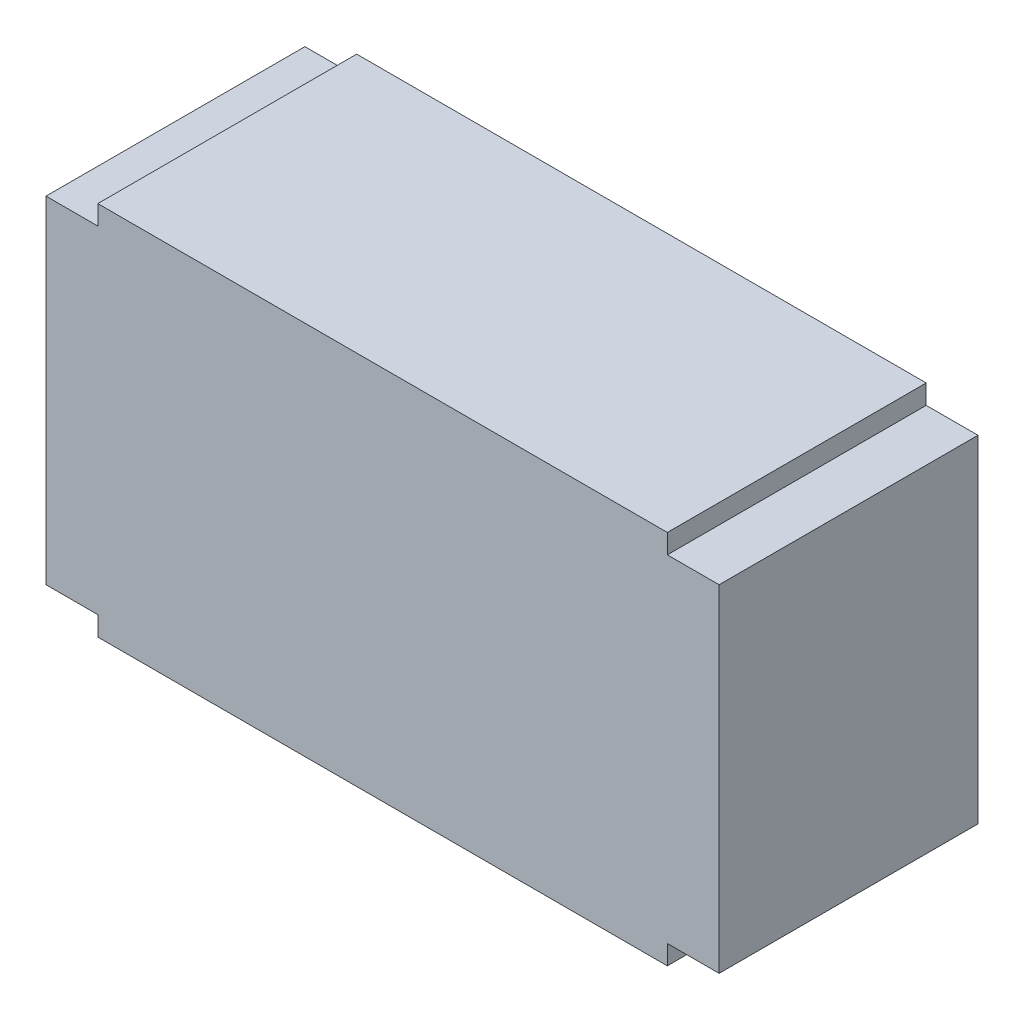
SolidWorks part; units mm, degrees
ref_plane "前视基准面" through (0, 0, 0) normal (0, 0, 1) x (1, 0, 0)
ref_plane "上视基准面" through (0, 0, 0) normal (0, 1, 0) x (1, 0, 0)
ref_plane "右视基准面" through (0, 0, 0) normal (1, 0, 0) x (0, 0, -1)
sketch "草图1" plane through (0, 0, 0) normal (0, 0, 1) x (1, 0, 0)
  line L0 (-1.3, 0.65) -> (-1.1, 0.65)
  line L1 (-1.1, 0.65) -> (-1.1, 0.725)
  line L2 (-1.1, 0.725) -> (1.1, 0.725)
  line L3 (1.1, 0.725) -> (1.1, 0.65)
  line L4 (1.1, 0.65) -> (1.3, 0.65)
  line L5 (1.3, 0.65) -> (1.3, -0.65)
  line L6 (1.3, -0.65) -> (1.1, -0.65)
  line L7 (1.1, -0.65) -> (1.1, -0.725)
  line L8 (1.1, -0.725) -> (-1.1, -0.725)
  line L9 (-1.1, -0.725) -> (-1.1, -0.65)
  line L10 (-1.1, -0.65) -> (-1.3, -0.65)
  line L11 (-1.3, -0.65) -> (-1.3, 0.65)
extrude "Component_Outline" add sketch "草图1" along normal blind 1 separate body
sketch3d "3D草图1"
  line L0 (0, 0, 0) -> (1, 0, 0)
  line L1 (0, 0, 0) -> (0, 1, 0)
  line L2 (0, 0, 0) -> (0, 0, 1)
  point P0 (0, 0, 0)
